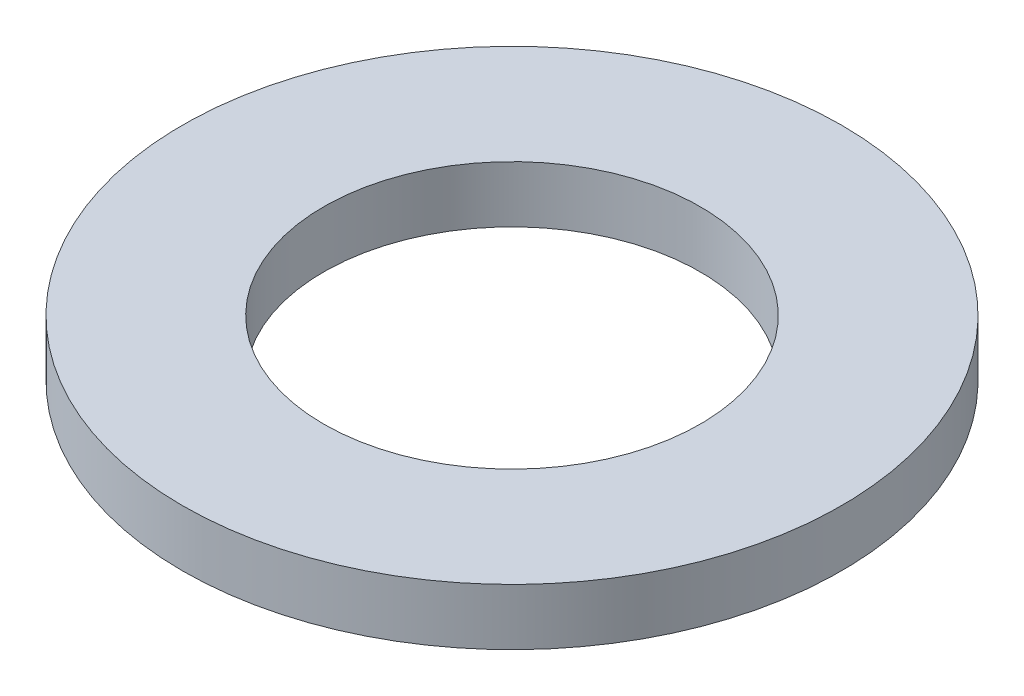
SolidWorks part; units mm, degrees
ref_plane "Front Plane" through (0, 0, 0) normal (0, 0, 1) x (1, 0, 0)
ref_plane "Top Plane" through (0, 0, 0) normal (0, 1, 0) x (1, 0, 0)
ref_plane "Right Plane" through (0, 0, 0) normal (1, 0, 0) x (0, 0, -1)
sketch "Sketch1" plane through (0, 0, 0) normal (0, 1, 0) x (1, 0, 0)
  circle A0 centre (0, 0) radius 7
  circle A1 centre (0, 0) radius 4
  dimension "D1" = 14
  dimension "D2" = 8
extrude "Boss-Extrude1" add sketch "Sketch1" along normal blind 1.2
